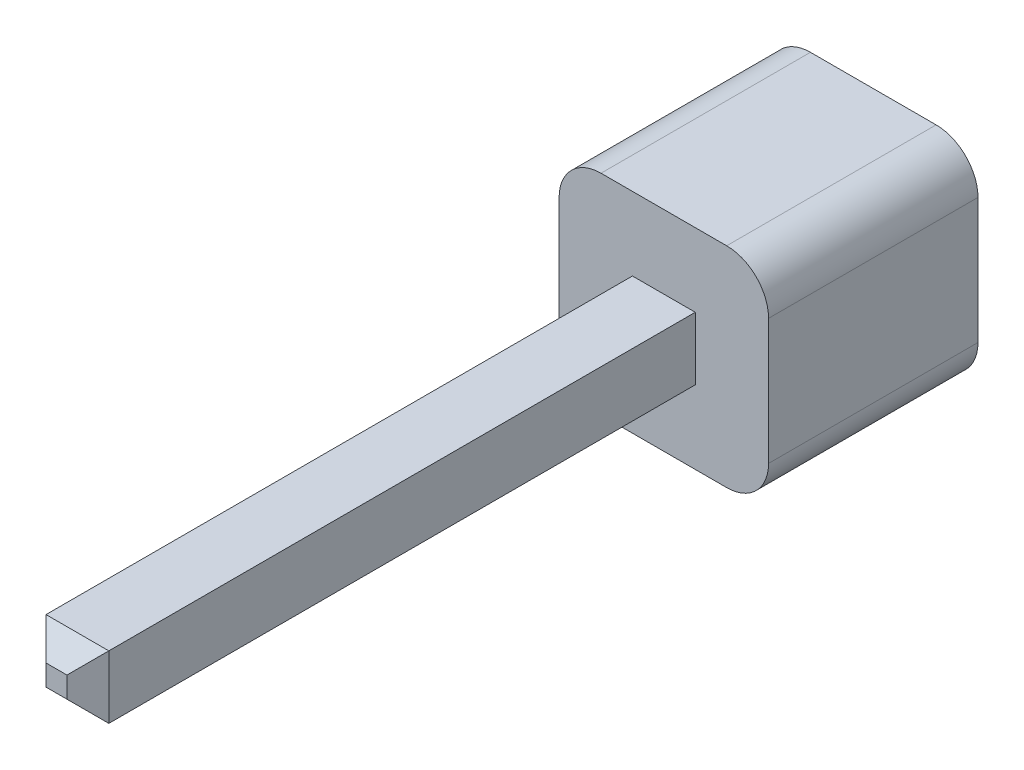
SolidWorks part; units mm, degrees
ref_plane "前视基准面" through (0, 0, 0) normal (0, 0, 1) x (1, 0, 0)
ref_plane "上视基准面" through (0, 0, 0) normal (0, 1, 0) x (1, 0, 0)
ref_plane "右视基准面" through (0, 0, 0) normal (1, 0, 0) x (0, 0, -1)
sketch "草图2" plane through (0, 0, 0) normal (0, 0, 1) x (1, 0, 0)
  line L1 (0, 0) -> (2.54, 0)
  line L2 (0, 0) -> (0, 2.54)
  line L3 (0, 2.54) -> (2.54, 2.54)
  line L4 (2.54, 0) -> (2.54, 2.54)
extrude "凸台-拉伸1" add sketch "草图2" against normal blind 2.54
fillet "圆角1" radius 0.508 4 edges at (2.54, 0, -1.27) (0, 0, -1.27) (0, 2.54, -1.27) (2.54, 2.54, -1.27)
sketch "草图3" plane through (0, 0, 0) normal (0, 0, 1) x (1, 0, 0)
  line L0 (0, 1.27) -> (2.54, 1.27) construction
  line L1 (0, 2.032) -> (0, 0.508) construction
  line L2 (2.54, 0.508) -> (2.54, 2.032) construction
  line L3 (1.27, 2.54) -> (1.27, 0) construction
  line L4 (2.032, 2.54) -> (0.508, 2.54) construction
  line L5 (0.508, 0) -> (2.032, 0) construction
  line L6 (1.27, 1.27) -> (1.651, 1.27) construction
  line L7 (1.651, 1.27) -> (1.651, 1.651)
  line L8 (1.651, 1.651) -> (0.889, 1.651)
  line L9 (0.889, 1.651) -> (0.889, 0.889)
  line L10 (0.889, 0.889) -> (1.651, 0.889)
  line L11 (1.651, 0.889) -> (1.651, 1.27)
extrude "凸台-拉伸2" add sketch "草图3" along normal blind 7.366
ref_plane "基准面1" through (1.651, 0, 0) normal (1, 0, 0) x (0, 0, -1)
sketch "草图4" plane through (1.651, 0, 0) normal (1, 0, 0) x (0, 0, -1)
  line L0 (-7.366, 1.27) -> (0, 1.27) construction
  line L1 (-7.366, 0.889) -> (-7.366, 1.651) construction
  line L2 (0, 0.889) -> (0, 1.651) construction
  line L3 (-7.366, 0.889) -> (-7.366, 1.143)
  line L4 (-7.366, 1.397) -> (-7.112, 1.651)
  line L5 (-7.366, 1.651) -> (0, 1.651) construction
  line L6 (-7.112, 1.651) -> (-7.366, 1.651)
  line L7 (-7.366, 1.651) -> (-7.366, 1.397)
  line L8 (-7.112, 0.889) -> (-7.366, 0.889)
  line L9 (-7.366, 1.143) -> (-7.112, 0.889)
extrude "切除-拉伸1" cut sketch "草图4" against normal through all
ref_plane "基准面2" through (0, 0.889, 0) normal (0, -1, 0) x (-1, 0, 0)
sketch "草图6" plane through (0, 0.889, 0) normal (0, -1, 0) x (-1, 0, 0)
  line L0 (-1.27, -7.112) -> (-1.27, -7.366) construction
  line L1 (-0.889, -7.112) -> (-1.651, -7.112) construction
  line L2 (-1.651, -7.366) -> (-0.889, -7.366) construction
  line L3 (-1.27, -7.366) -> (-1.143, -7.366) construction
  line L4 (-1.143, -7.366) -> (-0.889, -7.112)
  line L5 (-0.889, -7.112) -> (-0.889, -7.366)
  line L6 (-0.889, -7.366) -> (-1.143, -7.366)
  line L7 (-1.651, -7.366) -> (-1.397, -7.366)
  line L8 (-1.651, -7.112) -> (-1.651, -7.366)
  line L9 (-1.397, -7.366) -> (-1.651, -7.112)
extrude "切除-拉伸3" cut sketch "草图6" against normal through all
